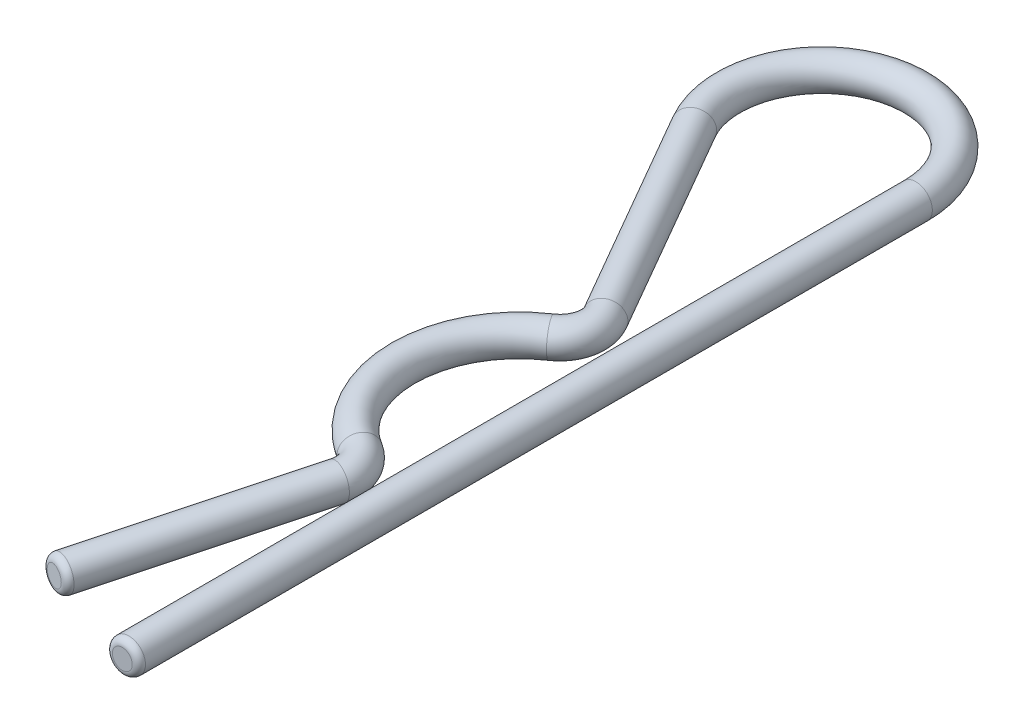
SolidWorks part; units mm, degrees
material "1.4000 (X6Cr13)"
ref_plane "Front Plane" through (0, 0, 0) normal (0, 0, 1) x (1, 0, 0)
ref_plane "Top Plane" through (0, 0, 0) normal (0, 1, 0) x (1, 0, 0)
ref_plane "Right Plane" through (0, 0, 0) normal (1, 0, 0) x (0, 0, -1)
sketch "Sketch1" plane through (0, 0, 0) normal (0, 1, 0) x (1, 0, 0)
  line L1 (0, -60) -> (0, 60)
  line L2 (-26.4511, 52.9199) -> (-8.1648, 21.2085)
  line L3 (-6.9838, -20.4434) -> (-16.0424, -54.2508)
  circle A1 centre (0, 0) radius 17.5 construction
  arc A2 (0, 60) -> (-26.4511, 52.9199) centre (-14.1731, 60) ccw
  arc A3 (-9.7193, 14.5528) -> (-9.1882, -14.8939) centre (0, 0) ccw
  arc A4 (-9.1882, -14.8939) -> (-6.9838, -20.4434) centre (-11.8134, -19.1493) cw
  arc A5 (-8.1648, 21.2085) -> (-9.7193, 14.5528) centre (-12.4963, 18.7108) cw
  dimension "D1" = 120
  dimension "D4" = 5
  dimension "D6" = 17.5
  dimension "D8" = 35
  dimension "D10" = 14.1731
  dimension "D5" = 35
  dimension "D2" = 60
  dimension "D3" = 15
  dimension "D7" = 36.6061
  dimension "D9" = 35
ref_plane "Plane1" through (0, 0, 60) normal (0, 0, -1) x (-1, 0, 0)
sketch "Sketch2" plane through (0, 0, 60) normal (0, 0, -1) x (-1, 0, 0)
  line L1 (17.5, 0) -> (-17.5, 0) construction
  circle A0 centre (0, 0) radius 2.5
  dimension "D1" = 5
sweep "Sweep2" add profiles "Sketch2" path "Sketch1"
fillet "Fillet1" radius 1 2 edges at (-2.5, 0, 60) (-13.6276, 0, 54.8978)
